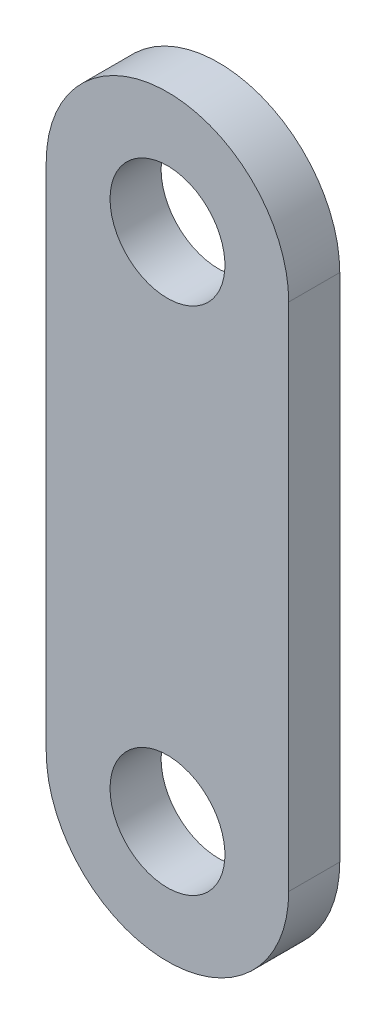
SolidWorks part; units mm, degrees
material "AISI 316 Stainless Steel Sheet (SS)"
ref_plane "Front Plane" through (0, 0, 0) normal (0, 0, 1) x (1, 0, 0)
ref_plane "Top Plane" through (0, 0, 0) normal (0, 1, 0) x (1, 0, 0)
ref_plane "Right Plane" through (0, 0, 0) normal (1, 0, 0) x (0, 0, -1)
sketch "Sketch1" plane through (0, 0, 0) normal (0, 0, 1) x (1, 0, 0)
  line L0 (0, -20) -> (0, 20) construction
  line L1 (-9.5, -20) -> (-9.5, 20)
  line L2 (9.5, -20) -> (9.5, 20)
  arc A0 (-9.5, -20) -> (9.5, -20) centre (0, -20) ccw
  arc A1 (9.5, 20) -> (-9.5, 20) centre (0, 20) ccw
  point P2 (0, 0)
  dimension "D1" = 40
  dimension "D2" = 19
extrude "Boss-Extrude1" add sketch "Sketch1" along normal blind 4
sketch "Sketch2" plane through (0, 0, 0) normal (0, 0, -1) x (-1, 0, 0)
  circle A0 centre (0, 20) radius 4.5
  circle A1 centre (0, -20) radius 4.5
  arc A2 (9.5, 20) -> (-9.5, 20) centre (0, 20) ccw construction
  arc A3 (-9.5, -20) -> (9.5, -20) centre (0, -20) ccw construction
  point P8 (0, 29.5)
  point P12 (0, -29.5)
  dimension "D1" = 9
  dimension "D2" = 9
  dimension "D3" = 9.5
  dimension "D4" = 9.5
extrude "Cut-Extrude1" cut sketch "Sketch2" against normal blind 4
